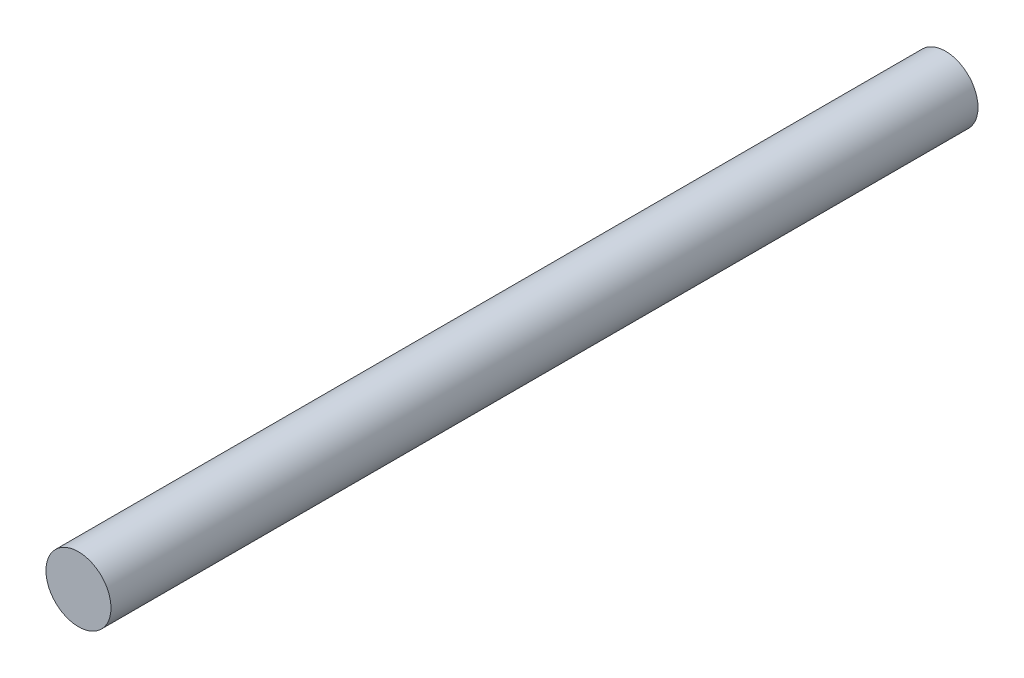
SolidWorks part; units mm, degrees
ref_plane "前视基准面" through (0, 0, 0) normal (0, 0, 1) x (1, 0, 0)
ref_plane "上视基准面" through (0, 0, 0) normal (0, 1, 0) x (1, 0, 0)
ref_plane "右视基准面" through (0, 0, 0) normal (1, 0, 0) x (0, 0, -1)
other "Configuration Table"
sketch "草图1" plane through (0, 0, 0) normal (0, 0, 1) x (1, 0, 0)
  circle A0 centre (0, 0) radius 3
extrude "凸台-拉伸1" add sketch "草图1" along normal blind 80
